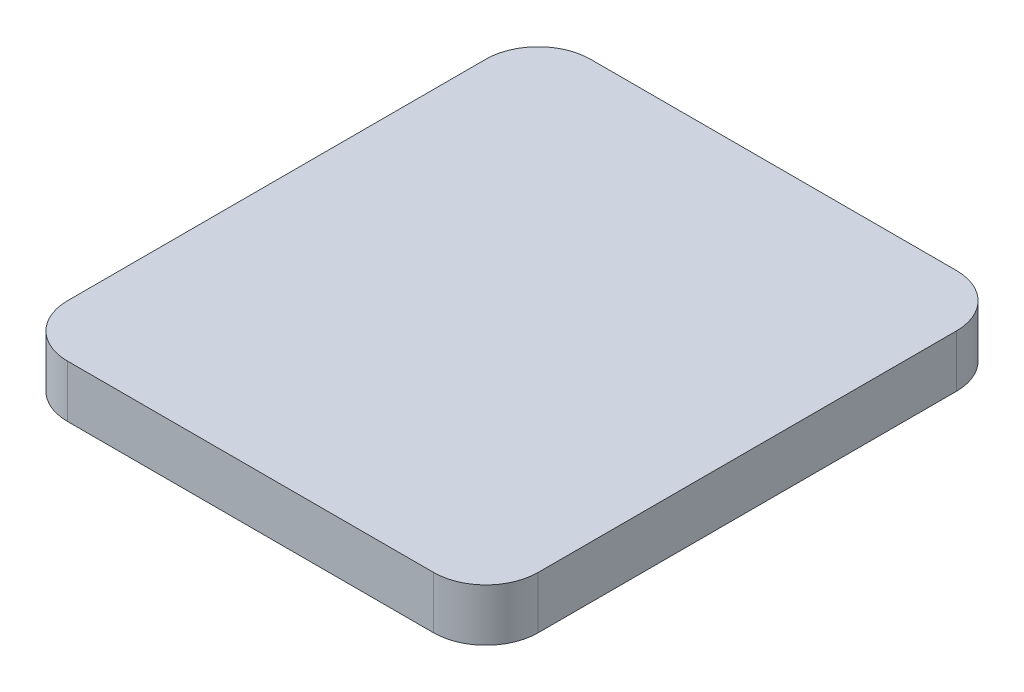
SolidWorks part; units mm, degrees
ref_plane "Front Plane" through (0, 0, 0) normal (0, 0, 1) x (1, 0, 0)
ref_plane "Top Plane" through (0, 0, 0) normal (0, 1, 0) x (1, 0, 0)
ref_plane "Right Plane" through (0, 0, 0) normal (1, 0, 0) x (0, 0, -1)
sketch "Sketch1" plane through (0, 0, 0) normal (0, 1, 0) x (1, 0, 0)
  line L1 (0, 0) -> (-90, 0)
  line L2 (0, 0) -> (0, -100)
  line L3 (0, -100) -> (-90, -100)
  line L4 (-90, 0) -> (-90, -100)
  point P5 (0, 0)
  dimension "D1" = 100
  dimension "D2" = 90
extrude "Boss-Extrude1" add sketch "Sketch1" along normal blind 10
fillet "Fillet1" radius 10 4 edges at (-90, 5, 0) (0, 5, 0) (0, 5, 100) (-90, 5, 100)
